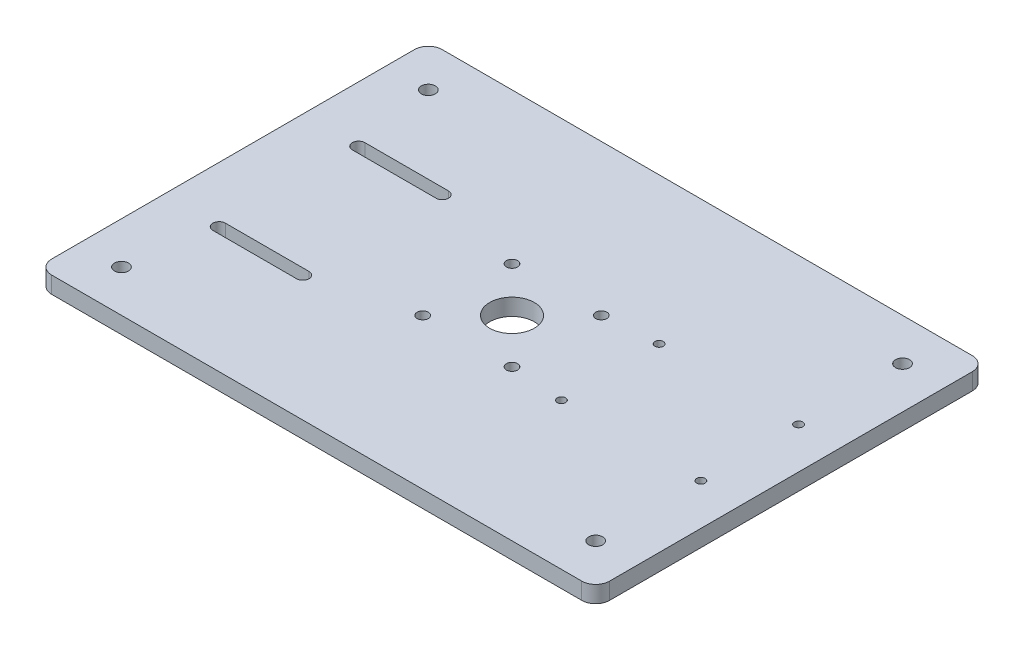
SolidWorks part; units mm, degrees
material "ABS"
ref_plane "Front Plane" through (0, 0, 0) normal (0, 0, 1) x (1, 0, 0)
ref_plane "Top Plane" through (0, 0, 0) normal (0, 1, 0) x (1, 0, 0)
ref_plane "Right Plane" through (0, 0, 0) normal (1, 0, 0) x (0, 0, -1)
sketch "Sketch2" plane through (0, 0, 0) normal (0, 1, 0) x (1, 0, 0)
  line L1 (-100, 70) -> (100, 70)
  line L2 (-100, 70) -> (-100, -70)
  line L3 (-100, -70) -> (100, -70)
  line L4 (100, 70) -> (100, -70)
  line L5 (-100, 70) -> (100, -70) construction
  line L6 (-100, -70) -> (100, 70) construction
  point P0 (0, 0)
  dimension "D1" = 200
  dimension "D2" = 140
extrude "Boss-Extrude1" add sketch "Sketch2" along normal blind 6
fillet "Fillet1" radius 5 4 edges at (-100, 3, -70) (-100, 3, 70) (100, 3, -70) (100, 3, 70)
sketch "Sketch3" plane through (0, 6, 0) normal (0, 1, 0) x (1, 0, 0)
  line L0 (-100, 65) -> (-100, -65) construction
  line L1 (95, 70) -> (-95, 70) construction
  circle A0 centre (-85, 55) radius 2.5
  circle A1 centre (-85, -55) radius 2.5
  circle A2 centre (85, -55) radius 2.5
  circle A3 centre (85, 55) radius 2.5
  point P20 (0, 0)
  dimension "D1" = 5
  dimension "D2" = 15
  dimension "D3" = 15
extrude "Cut-Extrude1" cut sketch "Sketch3" against normal through all
sketch "Sketch4" plane through (0, 6, 0) normal (0, 1, 0) x (1, 0, 0)
  circle A0 centre (0, 0) radius 8
  dimension "D1" = 16
extrude "Cut-Extrude2" cut sketch "Sketch4" against normal through all
sketch "Sketch5" plane through (0, 6, 0) normal (0, 1, 0) x (1, 0, 0)
  line L5 (-16, 16) -> (16, -16) construction
  line L6 (-16, -16) -> (16, 16) construction
  circle A2 centre (16, 16) radius 2
  circle A3 centre (16, -16) radius 2
  circle A4 centre (-16, -16) radius 2
  circle A5 centre (-16, 16) radius 2
  point P0 (0, 0)
  dimension "D1" = 32
  dimension "D2" = 32
  dimension "D3" = 4
  dimension "D4" = 4
  dimension "D5" = 4
  dimension "D6" = 4
  dimension "D7" = 16
  dimension "D8" = 16
extrude "Cut-Extrude3" cut sketch "Sketch5" against normal through all
sketch "Sketch6" plane through (0, 6, 0) normal (0, 1, 0) x (1, 0, 0)
  line L0 (-80, 25) -> (-50, 25) construction
  line L1 (-80, 27.25) -> (-50, 27.25)
  line L2 (-80, 22.75) -> (-50, 22.75)
  line L3 (-80, -25) -> (-50, -25) construction
  line L4 (-80, -22.75) -> (-50, -22.75)
  line L5 (-80, -27.25) -> (-50, -27.25)
  arc A0 (-80, 27.25) -> (-80, 22.75) centre (-80, 25) ccw
  arc A1 (-50, 22.75) -> (-50, 27.25) centre (-50, 25) ccw
  arc A2 (-80, -22.75) -> (-80, -27.25) centre (-80, -25) ccw
  arc A3 (-50, -27.25) -> (-50, -22.75) centre (-50, -25) ccw
  point P2 (-65, 25)
  point P10 (-65, -25)
  point P15 (0, 0)
  point P17 (-46.879, -20.7573)
  dimension "D1" = 30
  dimension "D2" = 4.5
  dimension "D3" = 65
  dimension "D4" = 25
  dimension "D5" = 65
  dimension "D6" = 30
  dimension "D7" = 4.5
  dimension "D8" = 25
extrude "Cut-Extrude4" cut sketch "Sketch6" against normal through all
sketch "Sketch7" plane through (0, 6, 0) normal (0, 1, 0) x (1, 0, 0)
  circle A0 centre (35.2223, -17.5) radius 1.5
  circle A1 centre (35.2223, 17.5) radius 1.5
  circle A2 centre (85.2223, 17.5) radius 1.5
  circle A3 centre (85.2223, -17.5) radius 1.5
  point P1 (0, 0)
  dimension "D4" = 3
  dimension "D5" = 3
  dimension "D6" = 3
  dimension "D7" = 3
  dimension "D2" = 35
  dimension "D3" = 50
extrude "Cut-Extrude5" cut sketch "Sketch7" against normal through all
